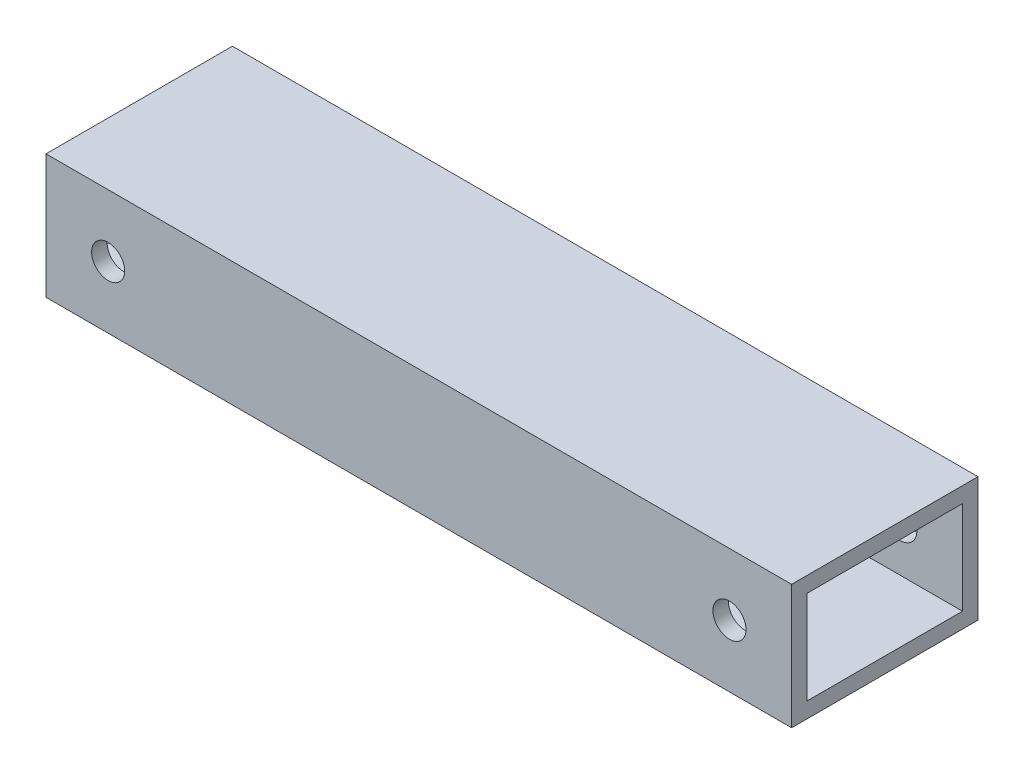
SolidWorks part; units mm, degrees
ref_plane "Front Plane" through (0, 0, 0) normal (0, 0, 1) x (1, 0, 0)
ref_plane "Top Plane" through (0, 0, 0) normal (0, 1, 0) x (1, 0, 0)
ref_plane "Right Plane" through (0, 0, 0) normal (1, 0, 0) x (0, 0, -1)
sketch "Sketch1" plane through (0, 0, 0) normal (1, 0, 0) x (0, 0, -1)
  line L1 (0, 0) -> (38.1, 0)
  line L2 (0, 0) -> (0, 25.4)
  line L3 (0, 25.4) -> (38.1, 25.4)
  line L4 (38.1, 0) -> (38.1, 25.4)
  dimension "D1" = 38.1
  dimension "D2" = 25.4
extrude "Extrude-Thin1" add sketch "Sketch1" along normal blind 152.4 thin thin type one direction reverse wall 3.175
sketch "Sketch2" plane through (0, 0, 0) normal (0, 0, 1) x (1, 0, 0)
  line L0 (0, 12.7) -> (12.7, 12.7) construction
  line L1 (0, 25.4) -> (0, 0) construction
  line L2 (152.4, 12.7) -> (139.7, 12.7) construction
  line L3 (152.4, 25.4) -> (152.4, 0) construction
  circle A0 centre (12.7, 12.7) radius 3.3782
  circle A1 centre (139.7, 12.7) radius 3.3782
  dimension "D1" = 6.7564
  dimension "D2" = 12.7
extrude "Cut-Extrude1" cut sketch "Sketch2" against normal through all
